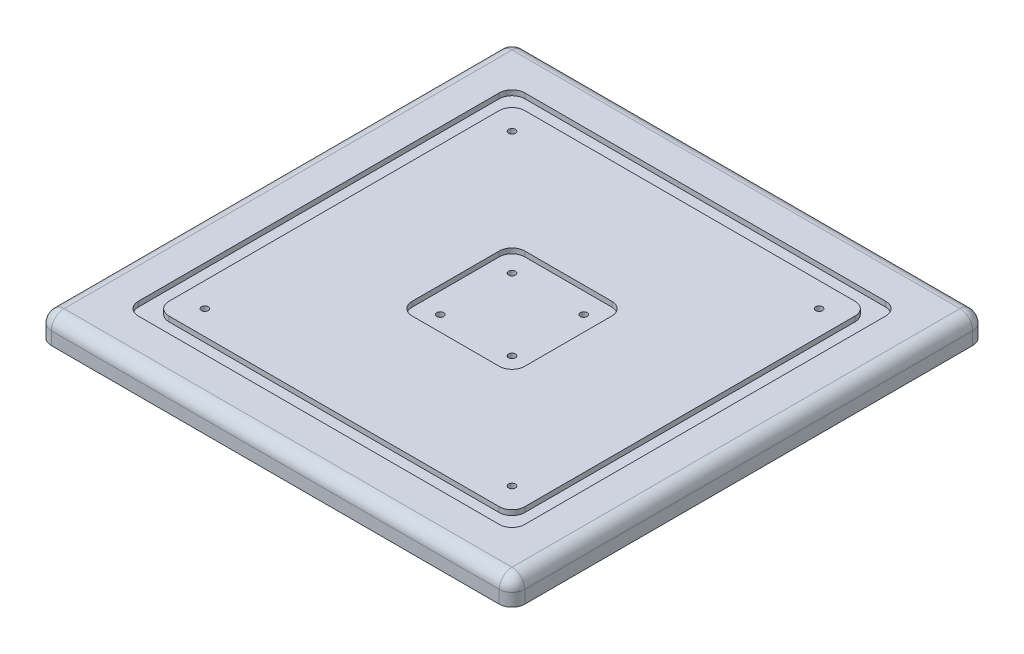
SolidWorks part; units mm, degrees
ref_plane "Front Plane" through (0, 0, 0) normal (0, 0, 1) x (1, 0, 0)
ref_plane "Top Plane" through (0, 0, 0) normal (0, 1, 0) x (1, 0, 0)
ref_plane "Right Plane" through (0, 0, 0) normal (1, 0, 0) x (0, 0, -1)
ref_plane "Plane1" through (0, 759.2984, 0) normal (0, -1, 0) x (-1, 0, 0)
sketch "Sketch2" plane through (0, 759.2984, 0) normal (0, -1, 0) x (-1, 0, 0)
  line L1 (-449.9756, -1350.7575) -> (-672.2256, -1350.7575)
  line L2 (-443.6256, -1344.4075) -> (-443.6256, -1122.1575)
  line L3 (-449.9756, -1115.8075) -> (-672.2256, -1115.8075)
  line L4 (-678.5756, -1344.4075) -> (-678.5756, -1122.1575)
  line L5 (-443.6256, -1350.7575) -> (-678.5756, -1115.8075) construction
  line L6 (-443.6256, -1115.8075) -> (-678.5756, -1350.7575) construction
  arc A0 (-443.6256, -1122.1575) -> (-449.9756, -1115.8075) centre (-449.9756, -1122.1575) ccw
  arc A1 (-449.9756, -1350.7575) -> (-443.6256, -1344.4075) centre (-449.9756, -1344.4075) ccw
  arc A2 (-672.2256, -1115.8075) -> (-678.5756, -1122.1575) centre (-672.2256, -1122.1575) ccw
  arc A3 (-672.2256, -1350.7575) -> (-678.5756, -1344.4075) centre (-672.2256, -1344.4075) cw
  point P0 (-561.1006, -1233.2825)
  dimension "D3" = 6.35
  dimension "D1" = 234.95
  dimension "D2" = 234.95
extrude "Boss-Extrude1" add sketch "Sketch2" along normal blind 12.7
fillet "Fillet1" radius 6.35 8 edges at (676.7157, 759.2984, 1348.8977) (678.5756, 759.2984, 1233.2825) (676.7157, 759.2984, 1117.6674) (561.1006, 759.2984, 1115.8075) (445.4855, 759.2984, 1117.6674) (443.6256, 759.2984, 1233.2825) (445.4855, 759.2984, 1348.8977) (561.1006, 759.2984, 1350.7575)
sketch "Sketch4" plane through (0, 759.2984, 0) normal (0, 1, 0) x (1, 0, 0)
  line L0 (561.1006, -1122.1575) -> (561.1006, -1344.4075) construction
  line L1 (672.2256, -1122.1575) -> (449.9756, -1122.1575) construction
  line L2 (449.9756, -1344.4075) -> (672.2256, -1344.4075) construction
  line L4 (471.5656, -1329.1675) -> (650.6356, -1329.1675)
  line L5 (465.2156, -1322.8175) -> (465.2156, -1143.7475)
  line L6 (471.5656, -1137.3975) -> (650.6356, -1137.3975)
  line L7 (656.9856, -1322.8175) -> (656.9856, -1143.7475)
  line L8 (465.2156, -1329.1675) -> (656.9856, -1137.3975) construction
  line L9 (465.2156, -1137.3975) -> (656.9856, -1329.1675) construction
  arc A0 (471.5656, -1329.1675) -> (465.2156, -1322.8175) centre (471.5656, -1322.8175) cw
  arc A1 (650.6356, -1329.1675) -> (656.9856, -1322.8175) centre (650.6356, -1322.8175) ccw
  arc A2 (650.6356, -1137.3975) -> (656.9856, -1143.7475) centre (650.6356, -1143.7475) cw
  arc A3 (465.2156, -1143.7475) -> (471.5656, -1137.3975) centre (471.5656, -1143.7475) cw
  point P6 (561.1006, -1233.2825)
  dimension "D3" = 6.35
  dimension "D1" = 191.77
  dimension "D2" = 191.77
extrude "Cut-Extrude1" cut sketch "Sketch4" against normal blind 2.54
sketch "Sketch5" plane through (0, 756.7584, 0) normal (0, 1, 0) x (1, 0, 0)
  line L8 (472.8356, -1321.5475) -> (649.3656, -1321.5475)
  line L9 (649.3656, -1321.5475) -> (649.3656, -1145.0175)
  line L10 (649.3656, -1145.0175) -> (472.8356, -1145.0175)
  line L11 (472.8356, -1145.0175) -> (472.8356, -1321.5475)
  line L12 (479.1856, -1321.5475) -> (643.0156, -1321.5475)
  line L13 (649.3656, -1315.1975) -> (649.3656, -1151.3675)
  line L14 (643.0156, -1145.0175) -> (479.1856, -1145.0175)
  line L15 (472.8356, -1151.3675) -> (472.8356, -1315.1975)
  arc A4 (649.3656, -1151.3675) -> (643.0156, -1145.0175) centre (643.0156, -1151.3675) ccw
  arc A5 (643.0156, -1321.5475) -> (649.3656, -1315.1975) centre (643.0156, -1315.1975) ccw
  arc A6 (479.1856, -1321.5475) -> (472.8356, -1315.1975) centre (479.1856, -1315.1975) cw
  arc A7 (479.1856, -1145.0175) -> (472.8356, -1151.3675) centre (479.1856, -1151.3675) ccw
  dimension "D2" = 6.35
  dimension "D1" = 7.62
extrude "Boss-Extrude2" add sketch "Sketch5" along normal up to surface (2.54 mm away) up to face at (561.1006, 759.2984, 1233.2825)
sketch "Sketch7" plane through (0, 746.5984, 0) normal (0, -1, 0) x (1, 0, 0)
  line L0 (561.1006, 1350.7575) -> (561.1006, 1115.8075) construction
  line L1 (672.2256, 1350.7575) -> (449.9756, 1350.7575) construction
  line L2 (449.9756, 1115.8075) -> (672.2256, 1115.8075) construction
  line L3 (443.6256, 1233.2825) -> (678.5756, 1233.2825) construction
  line L4 (443.6256, 1344.4075) -> (443.6256, 1122.1575) construction
  line L5 (678.5756, 1122.1575) -> (678.5756, 1344.4075) construction
  point P12 (484.9006, 1309.4825)
  point P13 (0, 0)
  point P14 (0, 0)
  point P15 (637.3006, 1309.4825)
  point P16 (0, 0)
  point P17 (637.3006, 1157.0825)
  point P18 (484.9006, 1157.0825)
  dimension "D1" = 76.2
  dimension "D2" = 76.2
hole_wizard "CSK for M3 Hex Socket Countersunk Cap Screw3" positions "Sketch7" profile "Sketch10" countersink size "M3" standard "ISO" end condition through all
sketch "Sketch10" plane through (484.9006, 746.5984, 1157.0825) normal (1, 0, 0) x (0, 0, -1)
  line L0 (0, 0) -> (0, 12.7)
  line L1 (0, 12.7) -> (1.7, 12.7)
  line L2 (1.7, 12.7) -> (1.7, 1.66)
  line L3 (1.7, 1.66) -> (3.36, 0)
  line L5 (3.36, 0) -> (0, 0)
  line L6 (-1.7, 1.66) -> (-3.36, 0) construction
  line L11 (0, -6.35) -> (0, 107.95) construction
  dimension "Thru Hole Dia." = 3.4
  dimension "Thru Hole Depth" = 12.7
  dimension "Near C'Sink Dia." = 6.72
  dimension "Near C'Sink Angle" = 90
sketch "Sketch11" plane through (0, 759.2984, 0) normal (0, 1, 0) x (1, 0, 0)
  line L0 (561.1006, -1145.0175) -> (561.1006, -1321.5475) construction
  line L3 (472.8356, -1233.2825) -> (649.3656, -1233.2825) construction
  line L4 (539.5106, -1261.2225) -> (582.6906, -1261.2225)
  line L5 (533.1606, -1254.8725) -> (533.1606, -1211.6925)
  line L6 (539.5106, -1205.3425) -> (582.6906, -1205.3425)
  line L7 (589.0406, -1254.8725) -> (589.0406, -1211.6925)
  line L8 (533.1606, -1261.2225) -> (589.0406, -1205.3425) construction
  line L9 (533.1606, -1205.3425) -> (589.0406, -1261.2225) construction
  line L10 (472.8356, -1151.3675) -> (472.8356, -1315.1975) construction
  line L11 (649.3656, -1151.3675) -> (649.3656, -1315.1975) construction
  line L12 (643.0156, -1321.5475) -> (479.1856, -1321.5475) construction
  line L13 (479.1856, -1145.0175) -> (643.0156, -1145.0175) construction
  arc A0 (582.6906, -1205.3425) -> (589.0406, -1211.6925) centre (582.6906, -1211.6925) cw
  arc A1 (582.6906, -1261.2225) -> (589.0406, -1254.8725) centre (582.6906, -1254.8725) ccw
  arc A2 (539.5106, -1261.2225) -> (533.1606, -1254.8725) centre (539.5106, -1254.8725) cw
  arc A3 (533.1606, -1211.6925) -> (539.5106, -1205.3425) centre (539.5106, -1211.6925) cw
  point P2 (0, 0)
  point P5 (0, 0)
  point P6 (561.1006, -1233.2825)
  point P23 (0, 0)
  point P32 (0, 0)
  dimension "D3" = 6.35
  dimension "D1" = 55.88
  dimension "D2" = 55.88
extrude "Cut-Extrude2" cut sketch "Sketch11" against normal up to surface (2.54 mm away) up to face at (561.1006, 756.7584, 1233.2825)
sketch "Sketch12" plane through (0, 746.5984, 0) normal (0, -1, 0) x (1, 0, 0)
  line L0 (443.6256, 1233.2825) -> (678.5756, 1233.2825) construction
  line L1 (443.6256, 1344.4075) -> (443.6256, 1122.1575) construction
  line L2 (678.5756, 1122.1575) -> (678.5756, 1344.4075) construction
  line L3 (561.1006, 1115.8075) -> (561.1006, 1350.7575) construction
  line L4 (449.9756, 1115.8075) -> (672.2256, 1115.8075) construction
  line L5 (672.2256, 1350.7575) -> (449.9756, 1350.7575) construction
  point P12 (0, 0)
  point P13 (543.3206, 1215.5025)
  point P14 (543.3206, 1251.0625)
  point P15 (0, 0)
  point P16 (578.8806, 1251.0625)
  point P17 (578.8806, 1215.5025)
  dimension "D1" = 17.78
  dimension "D2" = 17.78
hole_wizard "CSK for M3 Hex Socket Countersunk Cap Screw4" positions "Sketch12" profile "Sketch13" countersink size "M3" standard "ISO" end condition through all
sketch "Sketch13" plane through (578.8806, 746.5984, 1215.5025) normal (1, 0, 0) x (0, 0, -1)
  line L0 (0, 0) -> (0, 12.7)
  line L1 (0, 12.7) -> (1.7, 12.7)
  line L2 (1.7, 12.7) -> (1.7, 1.66)
  line L3 (1.7, 1.66) -> (3.36, 0)
  line L5 (3.36, 0) -> (0, 0)
  line L6 (-1.7, 1.66) -> (-3.36, 0) construction
  line L11 (0, -6.35) -> (0, 107.95) construction
  dimension "Thru Hole Dia." = 3.4
  dimension "Thru Hole Depth" = 12.7
  dimension "Near C'Sink Dia." = 6.72
  dimension "Near C'Sink Angle" = 90
